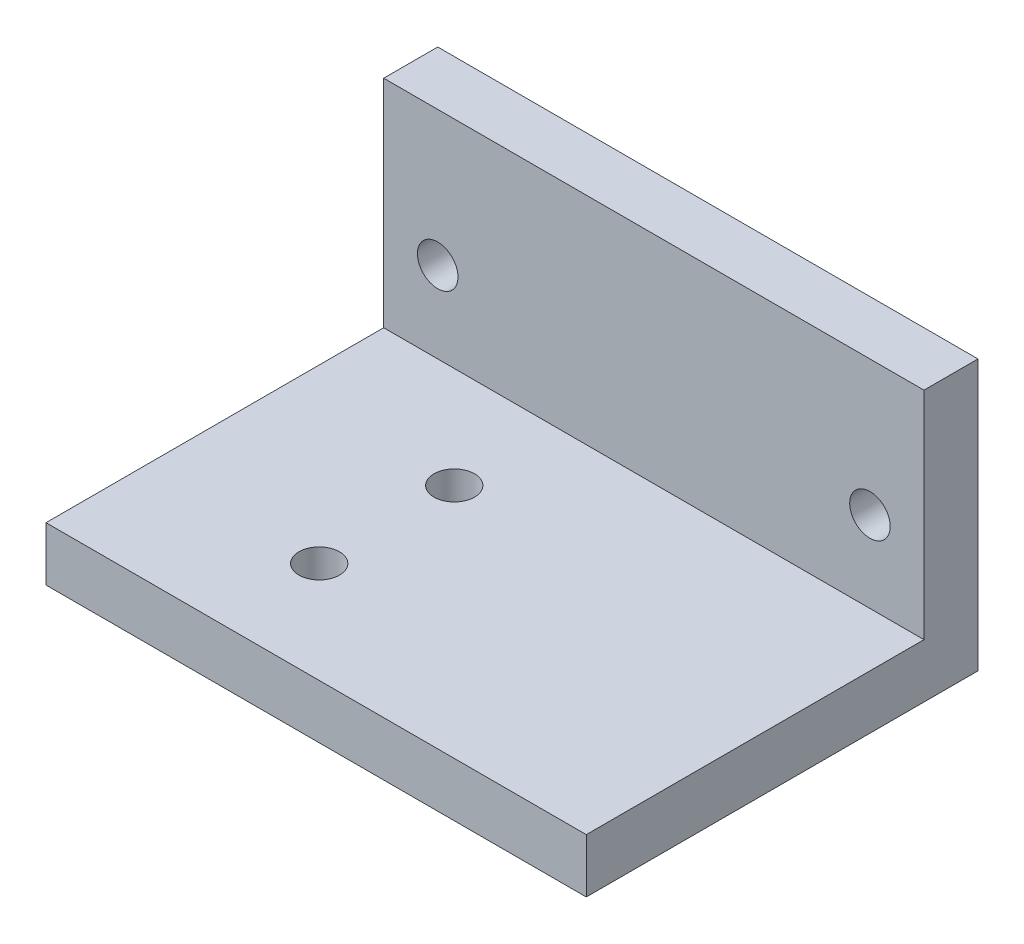
SolidWorks part; units mm, degrees
ref_plane "Спереди" through (0, 0, 0) normal (0, 0, 1) x (1, 0, 0)
ref_plane "Сверху" through (0, 0, 0) normal (0, 1, 0) x (1, 0, 0)
ref_plane "Справа" through (0, 0, 0) normal (1, 0, 0) x (0, 0, -1)
sketch "Эскиз1" plane through (0, 0, 0) normal (0, 0, 1) x (1, 0, 0)
  line L0 (0, -55) -> (0, 55) construction
  line L1 (-20, -10) -> (20, -10)
  line L2 (-20, -10) -> (-20, 10)
  line L3 (-20, 10) -> (20, 10)
  line L4 (20, -10) -> (20, 10)
  line L5 (-20, -10) -> (20, 10) construction
  line L6 (-20, 10) -> (20, -10) construction
  circle A0 centre (-16, 0) radius 1.5
  circle A2 centre (16, 0) radius 1.5
  point P0 (0, 0)
  point P12 (0, 0)
  dimension "D3" = 3
  dimension "D1" = 40
  dimension "D2" = 20
  dimension "D4" = 32
extrude "Бобышка-Вытянуть1" add sketch "Эскиз1" along normal blind 4
sketch "Эскиз2" plane through (0, -10, 0) normal (0, -1, 0) x (1, 0, 0)
  line L0 (-7.2741, 21.5) -> (-7.2741, 11.5) construction
  line L1 (-20, 4) -> (20, 4)
  line L2 (-20, 4) -> (-20, 29)
  line L3 (-20, 29) -> (20, 29)
  line L4 (20, 4) -> (20, 29)
  circle A0 centre (-7.2741, 21.5) radius 1.5
  circle A1 centre (-7.2741, 11.5) radius 1.5
  point P10 (-7.2741, 16.5)
  point P11 (-20, 16.5)
  dimension "D2" = 3
  dimension "D1" = 25
  dimension "D3" = 10
extrude "Бобышка-Вытянуть2" add sketch "Эскиз2" against normal blind 4
